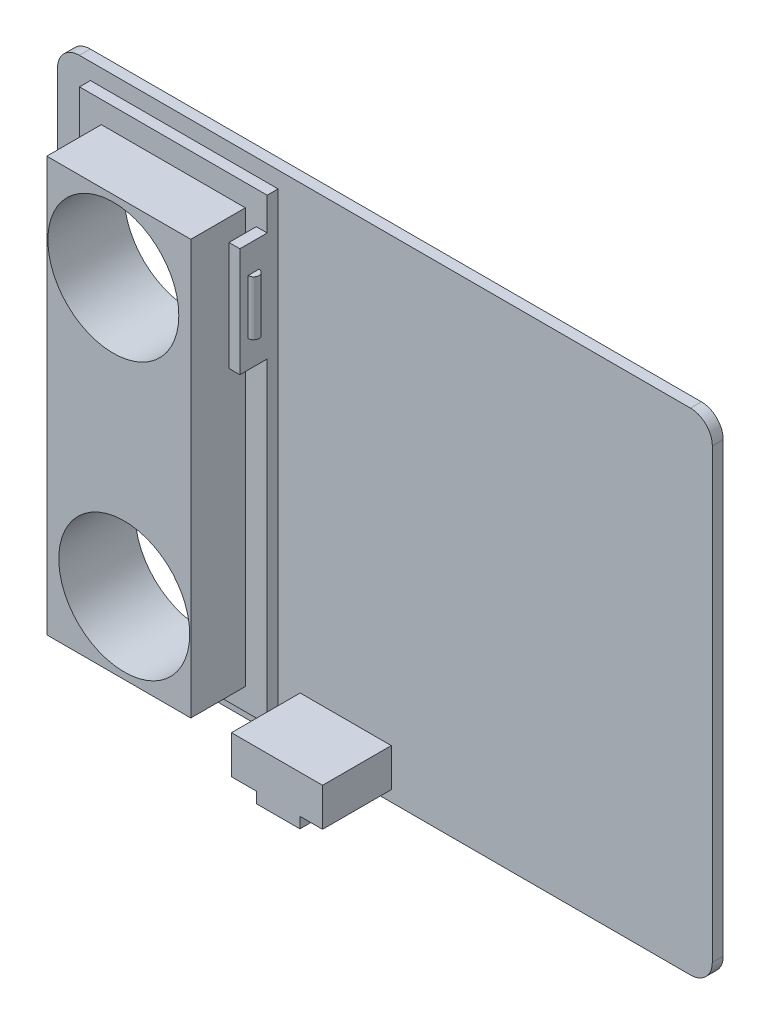
SolidWorks part; units mm, degrees
ref_plane "Front" through (0, 0, 0) normal (0, 0, 1) x (1, 0, 0)
ref_plane "Top" through (0, 0, 0) normal (0, 1, 0) x (1, 0, 0)
ref_plane "Right" through (0, 0, 0) normal (1, 0, 0) x (0, 0, -1)
sketch "草图1" plane through (0, 0, 0) normal (0, 0, 1) x (1, 0, 0)
  line L1 (0, 0) -> (17.2, 0)
  line L2 (0, 0) -> (0, 42)
  line L3 (0, 42) -> (17.2, 42)
  line L4 (17.2, 0) -> (17.2, 42)
  line L5 (2, 2) -> (15.2, 2)
  line L6 (2, 2) -> (2, 40)
  line L7 (2, 40) -> (15.2, 40)
  line L8 (15.2, 2) -> (15.2, 40)
  dimension "D1" = 42
  dimension "D2" = 17.2
  dimension "D3" = 2
  dimension "D4" = 2
  dimension "D5" = 2
  dimension "D6" = 2
extrude "凸台-拉伸1" add sketch "草图1" along normal blind 1
sketch "草图2" plane through (0, 0, 1) normal (0, 0, 1) x (1, 0, 0)
  line L0 (17.2, 0) -> (17.2, 42) construction
  line L1 (17.2, 39) -> (16.2, 39)
  line L2 (17.2, 39) -> (17.2, 29)
  line L3 (17.2, 29) -> (16.2, 29)
  line L4 (16.2, 39) -> (16.2, 29)
  line L5 (17.2, 42) -> (0, 42) construction
  line L6 (0, 42) -> (0, 0) construction
  line L7 (0, 3) -> (1, 3)
  line L8 (0, 3) -> (0, 13)
  line L9 (0, 13) -> (1, 13)
  line L10 (1, 3) -> (1, 13)
  line L11 (0, 0) -> (17.2, 0) construction
  dimension "D1" = 3
  dimension "D2" = 10
  dimension "D3" = 1
  dimension "D4" = 3
  dimension "D5" = 1
  dimension "D6" = 10
extrude "凸台-拉伸2" add sketch "草图2" along normal blind 2.5
ref_plane "基准面1" through (0, 34, 0) normal (0, -1, 0) x (-1, 0, 0)
sketch "草图3" plane through (0, 34, 0) normal (0, -1, 0) x (-1, 0, 0)
  line L0 (-17.2, -3.5) -> (-17.2, -1) construction
  line L1 (-17.2, -1.75) -> (-17.2, -2.75)
  arc A0 (-17.2, -1.75) -> (-17.2, -2.75) centre (-17.2, -2.25) ccw
  point P5 (-17.7, -2.25)
  dimension "D1" = 0.5
extrude "凸台-拉伸3" add sketch "草图3" along normal blind 2.5 and the other way blind 2.5
ref_plane "基准面2" through (0, 8, 0) normal (0, -1, 0) x (-1, 0, 0)
sketch "草图4" plane through (0, 8, 0) normal (0, -1, 0) x (-1, 0, 0)
  line L0 (0, -3.5) -> (0, -1) construction
  line L1 (0, -1.75) -> (0, -2.75)
  line L2 (0.25, -1.817) -> (0.25, -2.683)
  arc A0 (0, -1.75) -> (0.25, -1.817) centre (0, -2.25) cw
  arc A1 (0.25, -2.683) -> (0, -2.75) centre (0, -2.25) cw
  dimension "D1" = 0.5
  dimension "D2" = 0.25
extrude "凸台-拉伸4" add sketch "草图4" along normal blind 2.5 and the other way blind 2.5
sketch "草图5" plane through (0, 0, 0) normal (0, 0, -1) x (-1, 0, 0)
  line L1 (-57, -1.5) -> (3.0147, -1.5)
  line L2 (-57, -1.5) -> (-57, 43.5)
  line L3 (-57, 43.5) -> (3.0147, 43.5)
  line L4 (3.0147, -1.5) -> (3.0147, 43.5)
extrude "凸台-拉伸5" add sketch "草图5" along normal blind 1
fillet "圆角1" radius 2 4 edges at (-3.0147, -1.5, -0.5) (-3.0147, 43.5, -0.5) (57, 43.5, -0.5) (57, -1.5, -0.5)
sketch "草图6" plane through (0, 0, 0) normal (0, 0, 1) x (1, 0, 0)
  line L1 (27.775, -0.5) -> (19.225, -0.5)
  line L2 (27.775, -0.5) -> (27.775, 3)
  line L3 (27.775, 3) -> (19.225, 3)
  line L4 (19.225, -0.5) -> (19.225, 3)
extrude "凸台-拉伸6" add sketch "草图6" along normal blind 6.3
sketch "草图7" plane through (0, 0, 0) normal (0, 0, 1) x (1, 0, 0)
  line L0 (19.225, -0.5) -> (27.775, -0.5) construction
  line L1 (25.5022, -0.5) -> (21.5302, -0.5)
  line L2 (25.5022, -0.5) -> (25.5022, -1.5)
  line L3 (25.5022, -1.5) -> (21.5302, -1.5)
  line L4 (21.5302, -0.5) -> (21.5302, -1.5)
  line L5 (55, -1.5) -> (-1.0147, -1.5) construction
extrude "凸台-拉伸7" add sketch "草图7" along normal blind 6.3
sketch "草图8" plane through (0, 0, 0) normal (0, 0, 1) x (1, 0, 0)
  circle A0 centre (9.1, 8.6) radius 6
  circle A1 centre (8.1, 33.4) radius 6
  dimension "D1" = 12
  dimension "D2" = 12
extrude "切除-拉伸1" cut sketch "草图8" against normal through all
sketch "草图9" plane through (0, 0, 0) normal (0, 0, 1) x (1, 0, 0)
  line L4 (15.2, 40) -> (2, 40)
  line L5 (2, 40) -> (2, 2)
  line L6 (2, 2) -> (15.2, 2)
  line L7 (15.2, 2) -> (15.2, 40)
  line L8 (15.2, 40) -> (2, 40)
  line L9 (2, 40) -> (2, 2)
  line L10 (2, 2) -> (15.2, 2)
  line L11 (15.2, 2) -> (15.2, 40)
  circle A0 centre (9.1, 8.6) radius 6 construction
  circle A1 centre (9.1, 8.6) radius 6
  circle A2 centre (8.1, 33.4) radius 6 construction
  circle A3 centre (8.1, 33.4) radius 6
  dimension "D1" = 0
extrude "凸台-拉伸8" add sketch "草图9" along normal blind 6
fillet "圆角2" radius 0.15 2 edges at (-0.25, 8, 2.683) (-0.25, 8, 1.817)
sketch "草图10" plane through (27.775, 0, 0) normal (1, 0, 0) x (0, 0, -1)
  line L4 (0, -0.5) -> (0, 3)
  line L5 (0, 3) -> (-6.3, 3)
  line L6 (-6.3, 3) -> (-6.3, -0.5)
  line L7 (-6.3, -0.5) -> (0, -0.5)
  line L8 (0, -0.5) -> (0, 3)
  line L9 (0, 3) -> (-6.3, 3)
  line L10 (-6.3, 3) -> (-6.3, -0.5)
  line L11 (-6.3, -0.5) -> (0, -0.5)
  dimension "D1" = 0
extrude "切除-拉伸2" cut sketch "草图10" against normal blind 0.2
